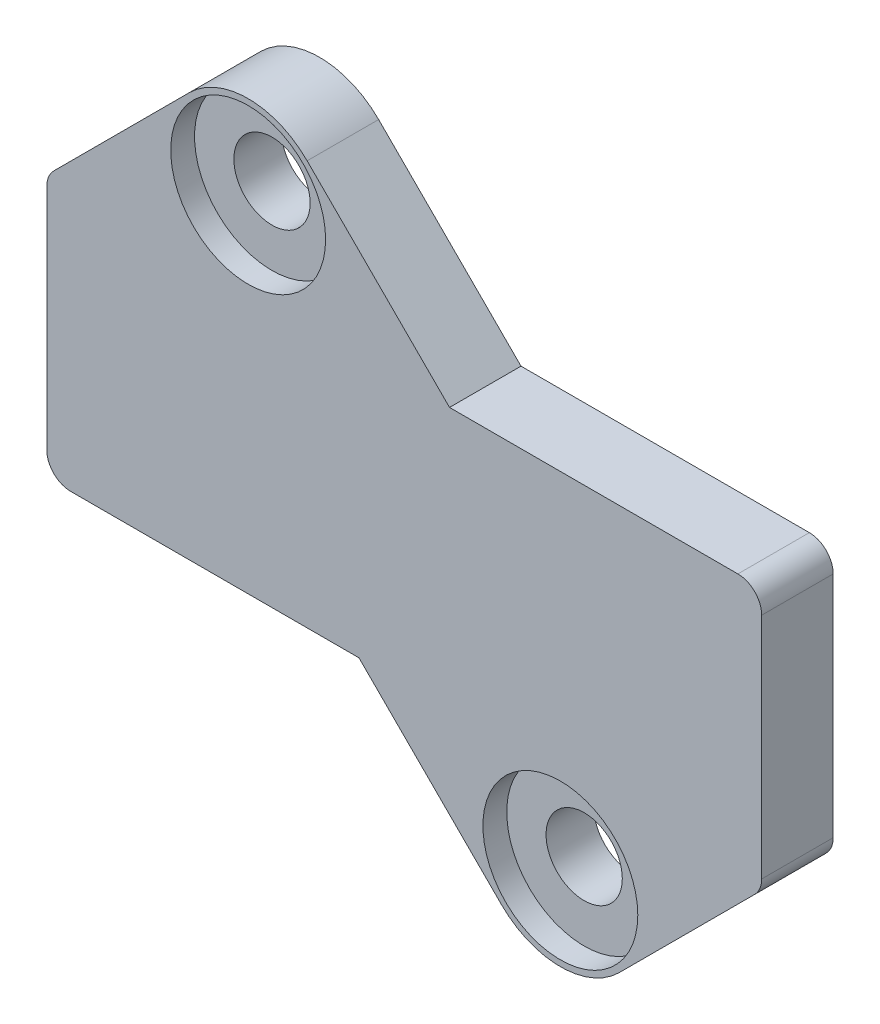
SolidWorks part; units mm, degrees
material "ABS"
ref_plane "前视基准面" through (0, 0, 0) normal (0, 0, 1) x (1, 0, 0)
ref_plane "上视基准面" through (0, 0, 0) normal (0, 1, 0) x (1, 0, 0)
ref_plane "右视基准面" through (0, 0, 0) normal (1, 0, 0) x (0, 0, -1)
other "Configuration Table"
sketch "草图1" plane through (0, 0, 0) normal (0, 0, 1) x (1, 0, 0)
  line B0 (15, 5.5) -> (1.8995, 5.5)
  line B1 (-15, 5.5) -> (-15, -5.5)
  line B2 (-15, -5.5) -> (-1.8995, -5.5)
  line B3 (15, -5.5) -> (15, 5.5)
  line B4 (-15, 5.5) -> (-9.0251, 11.4749)
  line B5 (1.8995, 5.5) -> (-4.0754, 11.4749)
  line B6 (15, -5.5) -> (9.0251, -11.4749)
  line B7 (-1.8995, -5.5) -> (4.0754, -11.4749)
  line B8 (15.5, 6) -> (2.1066, 6) construction
  line B9 (2.1066, 6) -> (-3.7218, 11.8284) construction
  line B10 (-15.5, 5.7071) -> (-9.3787, 11.8284) construction
  line B11 (-15.5, 5.7071) -> (-15.5, -6) construction
  line B12 (-15.5, -6) -> (-2.1066, -6) construction
  line B13 (-2.1066, -6) -> (3.7218, -11.8284) construction
  line B14 (15.5, -5.7071) -> (9.3787, -11.8284) construction
  line B15 (15.5, -5.7071) -> (15.5, 6) construction
  line B16 (15, 5.5) -> (-15, -5.5) construction
  arc B17 (-4.0754, 11.4749) -> (-9.0251, 11.4749) centre (-6.5503, 9) ccw
  arc B18 (4.0754, -11.4749) -> (9.0251, -11.4749) centre (6.5503, -9) ccw
  arc B19 (-3.7218, 11.8284) -> (-9.3787, 11.8284) centre (-6.5503, 9) ccw construction
  arc B20 (3.7218, -11.8284) -> (9.3787, -11.8284) centre (6.5503, -9) ccw construction
sketch_block_instance "块4-1"
sketch_block "块4" parameters "D1"=7, "D2"=45, "D3"=45, "D4"=45, "D5"=45, "D6"=11
extrude "凸台-拉伸1" add sketch "草图1" along normal blind 3
sketch "草图3" plane through (0, 0, 3) normal (0, 0, 1) x (1, 0, 0)
  circle A0 centre (-6.5503, 9) radius 3.25
  circle A1 centre (6.5503, -9) radius 3.25
  dimension "D1" = 6.5
extrude "切除-拉伸1" cut sketch "草图3" against normal blind 1
fillet "圆角1" radius 1 4 edges at (15, 5.5, 1.5) (15, -5.5, 1.5) (-15, -5.5, 1.5) (-15, 5.5, 1.5)
sketch "草图6" plane through (0, 0, 3) normal (0, 0, 1) x (1, 0, 0)
  circle A0 centre (-6.5503, 9) radius 1.6
  circle A1 centre (6.5503, -9) radius 1.6
  dimension "D1" = 3.2
extrude "切除-拉伸3" cut sketch "草图6" against normal through all
